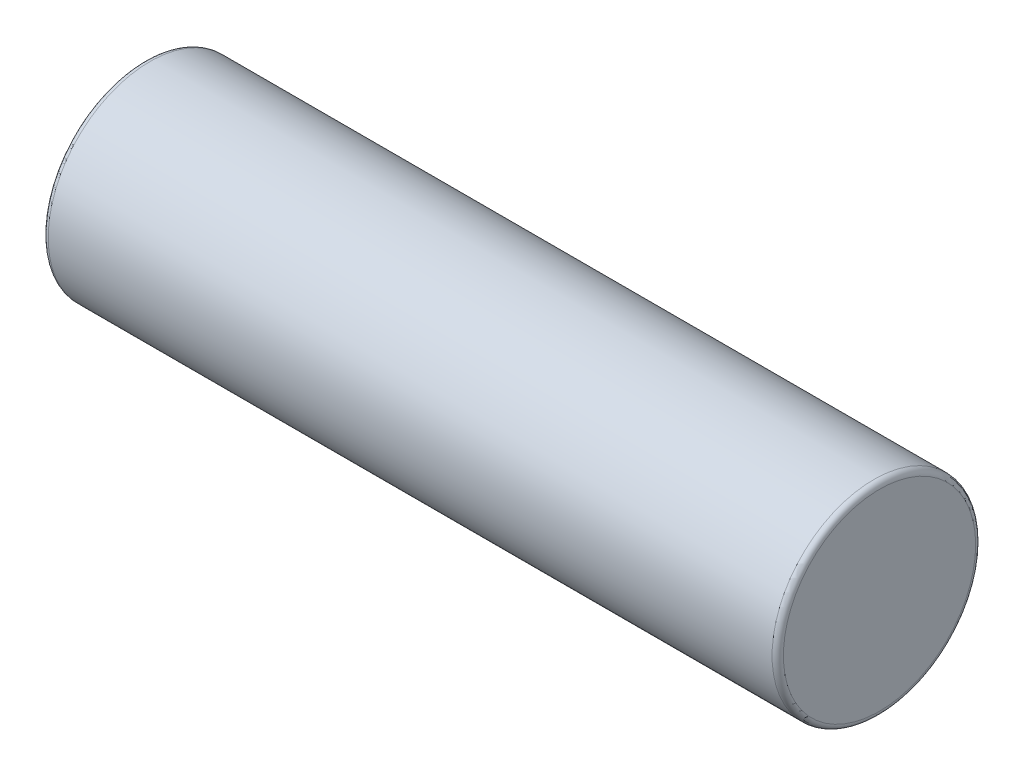
SolidWorks part; units mm, degrees
ref_plane "Спереди" through (0, 0, 0) normal (0, 0, 1) x (1, 0, 0)
ref_plane "Сверху" through (0, 0, 0) normal (0, 1, 0) x (1, 0, 0)
ref_plane "Справа" through (0, 0, 0) normal (1, 0, 0) x (0, 0, -1)
sketch "Эскиз2" plane through (0, 0, 0) normal (1, 0, 0) x (0, 0, -1)
  circle A0 centre (0, 0) radius 9
  dimension "D1" = 18
extrude "Бобышка-Вытянуть1" add sketch "Эскиз2" against normal blind 65
fillet "Скругление1" radius 0.5 2 edges at (0, 0, -9) (-65, 0, -9)
